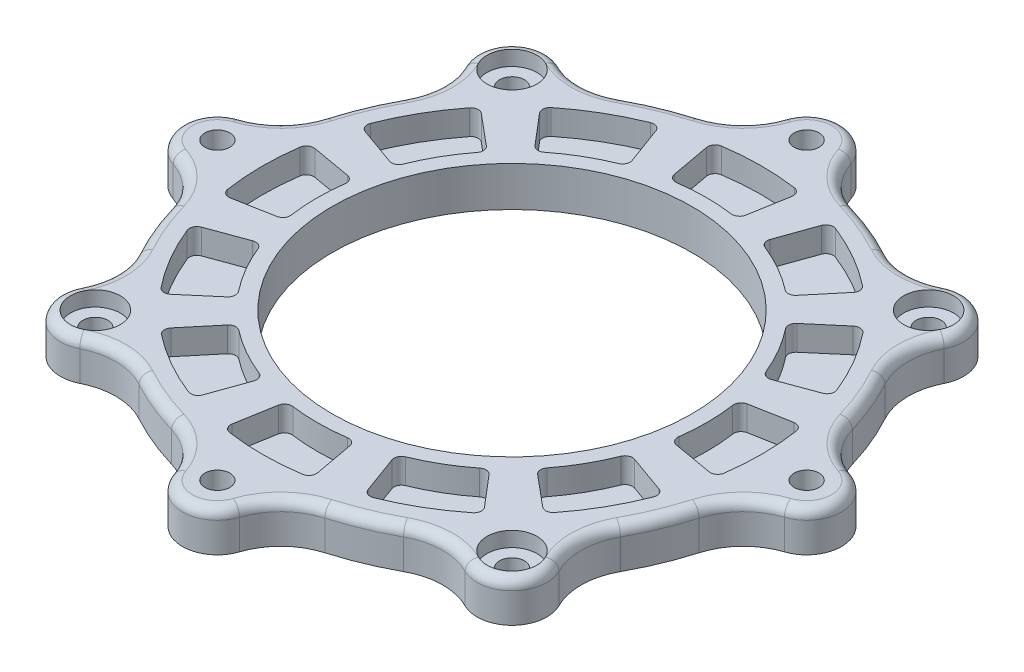
SolidWorks part; units mm, degrees
ref_plane "Front Plane" through (0, 0, 0) normal (0, 0, 1) x (1, 0, 0)
ref_plane "Top Plane" through (0, 0, 0) normal (0, 1, 0) x (1, 0, 0)
ref_plane "Right Plane" through (0, 0, 0) normal (1, 0, 0) x (0, 0, -1)
other "Graphic1"
other "Graphic (Closed) -1"
sketch "Sketch1" plane through (0, 0, 0) normal (0, 1, 0) x (1, 0, 0)
  line L0 (-43.8844, 40.4693) -> (-39.5542, 42.9693)
  circle A0 centre (0, 0) radius 36
  arc A1 (-48.2016, 26.4879) -> (-52.8134, 15.3539) centre (0, 0) ccw
  circle A2 centre (-41.7193, 41.7193) radius 2.5
  arc A3 (-38.5796, 47.9757) -> (-47.9757, 38.5796) centre (-41.7193, 41.7193) ccw
  arc A4 (-47.9757, 38.5796) -> (-48.2016, 26.4879) centre (-59.5947, 32.7487) cw
  arc A5 (-38.5796, 47.9757) -> (-26.4879, 48.2016) centre (-32.7487, 59.5947) ccw
  circle A6 centre (0, 59) radius 2.5
  arc A7 (-6.644, 61.2038) -> (-15.3539, 52.8134) centre (-18.983, 65.2966) cw
  arc A8 (6.644, 61.2038) -> (-6.644, 61.2038) centre (0, 59) ccw
  arc A9 (6.644, 61.2038) -> (15.3539, 52.8134) centre (18.983, 65.2966) ccw
  circle A10 centre (41.7193, 41.7193) radius 2.5
  arc A11 (38.5796, 47.9757) -> (26.4879, 48.2016) centre (32.7487, 59.5947) cw
  arc A12 (47.9757, 38.5796) -> (38.5796, 47.9757) centre (41.7193, 41.7193) ccw
  arc A13 (47.9757, 38.5796) -> (48.2016, 26.4879) centre (59.5947, 32.7487) ccw
  circle A14 centre (59, 0) radius 2.5
  arc A15 (61.2038, 6.644) -> (52.8134, 15.3539) centre (65.2966, 18.983) cw
  arc A16 (61.2038, -6.644) -> (61.2038, 6.644) centre (59, 0) ccw
  arc A17 (61.2038, -6.644) -> (52.8134, -15.3539) centre (65.2966, -18.983) ccw
  circle A18 centre (41.7193, -41.7193) radius 2.5
  arc A19 (47.9757, -38.5796) -> (48.2016, -26.4879) centre (59.5947, -32.7487) cw
  arc A20 (38.5796, -47.9757) -> (47.9757, -38.5796) centre (41.7193, -41.7193) ccw
  arc A21 (38.5796, -47.9757) -> (26.4879, -48.2016) centre (32.7487, -59.5947) ccw
  circle A22 centre (0, -59) radius 2.5
  arc A23 (6.644, -61.2038) -> (15.3539, -52.8134) centre (18.983, -65.2966) cw
  arc A24 (-6.644, -61.2038) -> (6.644, -61.2038) centre (0, -59) ccw
  arc A25 (-6.644, -61.2038) -> (-15.3539, -52.8134) centre (-18.983, -65.2966) ccw
  circle A26 centre (-41.7193, -41.7193) radius 2.5
  arc A27 (-38.5796, -47.9757) -> (-26.4879, -48.2016) centre (-32.7487, -59.5947) cw
  arc A28 (-47.9757, -38.5796) -> (-38.5796, -47.9757) centre (-41.7193, -41.7193) ccw
  arc A29 (-47.9757, -38.5796) -> (-48.2016, -26.4879) centre (-59.5947, -32.7487) ccw
  circle A30 centre (-59, 0) radius 2.5
  arc A31 (-61.2038, -6.644) -> (-52.8134, -15.3539) centre (-65.2966, -18.983) cw
  arc A32 (-61.2038, 6.644) -> (-61.2038, -6.644) centre (-59, 0) ccw
  arc A33 (-61.2038, 6.644) -> (-52.8134, 15.3539) centre (-65.2966, 18.983) ccw
  arc A34 (-52.8134, -15.3539) -> (-48.2016, -26.4879) centre (0, 0) ccw
  arc A35 (-26.4879, -48.2016) -> (-15.3539, -52.8134) centre (0, 0) ccw
  arc A36 (15.3539, -52.8134) -> (26.4879, -48.2016) centre (0, 0) ccw
  arc A37 (48.2016, -26.4879) -> (52.8134, -15.3539) centre (0, 0) ccw
  arc A38 (52.8134, 15.3539) -> (48.2016, 26.4879) centre (0, 0) ccw
  arc A39 (26.4879, 48.2016) -> (15.3539, 52.8134) centre (0, 0) ccw
  arc A40 (-15.3539, 52.8134) -> (-26.4879, 48.2016) centre (0, 0) ccw
  point P74 (0, 0)
  dimension "D1" = 13
  dimension "D2" = 8
extrude "Boss-Extrude1" add sketch "Sketch1" against normal blind 8 contours A7 A40 A5 A3 A4 A1 A33 A32 A31 A34 A29 A28 A27 A35 A25 A24 A23 A36 A21 A20 A19 A37 A17 A16 A15 A38 A13 A12 A11 A39 A9 A8 A0 A2 A6 A10 A14 A18 A22 A26 A30
sketch "Sketch2" plane through (0, 0, 0) normal (0, 1, 0) x (1, 0, 0)
  line L0 (-45.6653, 16.2691) -> (-38.1249, 13.5827)
  line L1 (-37.2162, 31.0637) -> (-31.071, 25.9344)
  line L2 (-31.4127, 36.9221) -> (-26.2258, 30.8254)
  line L3 (-16.6983, 45.5101) -> (-13.9411, 37.9954)
  line L4 (-8.7432, 47.6818) -> (-7.2995, 39.8085)
  line L5 (8.2939, 47.762) -> (6.9244, 39.8755)
  line L6 (16.2691, 45.6653) -> (13.5827, 38.1249)
  line L7 (31.0637, 37.2162) -> (25.9344, 31.071)
  line L8 (36.9221, 31.4127) -> (30.8254, 26.2258)
  line L9 (45.5101, 16.6983) -> (37.9954, 13.9411)
  line L10 (47.6818, 8.7432) -> (39.8085, 7.2995)
  line L11 (47.762, -8.2939) -> (39.8755, -6.9244)
  line L12 (45.6653, -16.2691) -> (38.1249, -13.5827)
  line L13 (37.2162, -31.0637) -> (31.071, -25.9344)
  line L14 (31.4127, -36.9221) -> (26.2258, -30.8254)
  line L15 (16.6983, -45.5101) -> (13.9411, -37.9954)
  line L16 (8.7432, -47.6818) -> (7.2995, -39.8085)
  line L17 (-8.2939, -47.762) -> (-6.9244, -39.8755)
  line L18 (-16.2691, -45.6653) -> (-13.5827, -38.1249)
  line L19 (-31.0637, -37.2162) -> (-25.9344, -31.071)
  line L20 (-36.9221, -31.4127) -> (-30.8254, -26.2258)
  line L21 (-45.5101, -16.6983) -> (-37.9954, -13.9411)
  line L22 (-47.6818, -8.7432) -> (-39.8085, -7.2995)
  line L23 (-47.762, 8.2939) -> (-39.8755, 6.9244)
  arc A0 (-30.8458, 23.865) -> (-36.2281, 14.4403) centre (0, 0) ccw
  arc A2 (-39.3581, 30.8373) -> (-46.5586, 18.229) centre (0, 0) ccw
  arc A3 (-45.6653, 16.2691) -> (-46.5586, 18.229) centre (-45.1619, 17.6821) cw
  arc A4 (-38.1249, 13.5827) -> (-36.2281, 14.4403) centre (-37.6215, 14.9957) ccw
  arc A5 (-31.071, 25.9344) -> (-30.8458, 23.865) centre (-32.0322, 24.7828) cw
  arc A6 (-37.2162, 31.0637) -> (-39.3581, 30.8373) centre (-38.1774, 29.9121) ccw
  arc A7 (-18.6665, 46.3849) -> (-31.2065, 39.066) centre (0, 0) ccw
  arc A8 (-16.6983, 45.5101) -> (-18.6665, 46.3849) centre (-18.1065, 44.9934) ccw
  arc A9 (-31.4127, 36.9221) -> (-31.2065, 39.066) centre (-30.2703, 37.8941) cw
  arc A10 (-26.2258, 30.8254) -> (-24.1543, 30.6197) centre (-25.0833, 31.7974) ccw
  arc A11 (-14.7808, 36.0906) -> (-24.1543, 30.6197) centre (0, 0) ccw
  arc A12 (-13.9411, 37.9954) -> (-14.7808, 36.0906) centre (-15.3493, 37.4787) cw
  arc A13 (7.0268, 49.5038) -> (-7.4926, 49.4354) centre (0, 0) ccw
  arc A14 (8.2939, 47.762) -> (7.0268, 49.5038) centre (6.816, 48.0187) ccw
  arc A15 (-8.7432, 47.6818) -> (-7.4926, 49.4354) centre (-7.2678, 47.9524) cw
  arc A16 (-7.2995, 39.8085) -> (-5.6084, 38.5946) centre (-5.8241, 40.079) ccw
  arc A17 (5.2448, 38.6457) -> (-5.6084, 38.5946) centre (0, 0) ccw
  arc A18 (6.9244, 39.8755) -> (5.2448, 38.6457) centre (5.4465, 40.1321) cw
  arc A19 (30.8373, 39.3581) -> (18.229, 46.5586) centre (0, 0) ccw
  arc A20 (31.0637, 37.2162) -> (30.8373, 39.3581) centre (29.9121, 38.1774) ccw
  arc A21 (16.2691, 45.6653) -> (18.229, 46.5586) centre (17.6821, 45.1619) cw
  arc A22 (13.5827, 38.1249) -> (14.4403, 36.2281) centre (14.9957, 37.6215) ccw
  arc A23 (23.865, 30.8458) -> (14.4403, 36.2281) centre (0, 0) ccw
  arc A24 (25.9344, 31.071) -> (23.865, 30.8458) centre (24.7828, 32.0322) cw
  arc A25 (46.3849, 18.6665) -> (39.066, 31.2065) centre (0, 0) ccw
  arc A26 (45.5101, 16.6983) -> (46.3849, 18.6665) centre (44.9934, 18.1065) ccw
  arc A27 (36.9221, 31.4127) -> (39.066, 31.2065) centre (37.8941, 30.2703) cw
  arc A28 (30.8254, 26.2258) -> (30.6197, 24.1543) centre (31.7974, 25.0833) ccw
  arc A29 (36.0906, 14.7808) -> (30.6197, 24.1543) centre (0, 0) ccw
  arc A30 (37.9954, 13.9411) -> (36.0906, 14.7808) centre (37.4787, 15.3493) cw
  arc A31 (49.5038, -7.0268) -> (49.4354, 7.4926) centre (0, 0) ccw
  arc A32 (47.762, -8.2939) -> (49.5038, -7.0268) centre (48.0187, -6.816) ccw
  arc A33 (47.6818, 8.7432) -> (49.4354, 7.4926) centre (47.9524, 7.2678) cw
  arc A34 (39.8085, 7.2995) -> (38.5946, 5.6084) centre (40.079, 5.8241) ccw
  arc A35 (38.6457, -5.2448) -> (38.5946, 5.6084) centre (0, 0) ccw
  arc A36 (39.8755, -6.9244) -> (38.6457, -5.2448) centre (40.1321, -5.4465) cw
  arc A37 (39.3581, -30.8373) -> (46.5586, -18.229) centre (0, 0) ccw
  arc A38 (37.2162, -31.0637) -> (39.3581, -30.8373) centre (38.1774, -29.9121) ccw
  arc A39 (45.6653, -16.2691) -> (46.5586, -18.229) centre (45.1619, -17.6821) cw
  arc A40 (38.1249, -13.5827) -> (36.2281, -14.4403) centre (37.6215, -14.9957) ccw
  arc A41 (30.8458, -23.865) -> (36.2281, -14.4403) centre (0, 0) ccw
  arc A42 (31.071, -25.9344) -> (30.8458, -23.865) centre (32.0322, -24.7828) cw
  arc A43 (18.6665, -46.3849) -> (31.2065, -39.066) centre (0, 0) ccw
  arc A44 (16.6983, -45.5101) -> (18.6665, -46.3849) centre (18.1065, -44.9934) ccw
  arc A45 (31.4127, -36.9221) -> (31.2065, -39.066) centre (30.2703, -37.8941) cw
  arc A46 (26.2258, -30.8254) -> (24.1543, -30.6197) centre (25.0833, -31.7974) ccw
  arc A47 (14.7808, -36.0906) -> (24.1543, -30.6197) centre (0, 0) ccw
  arc A48 (13.9411, -37.9954) -> (14.7808, -36.0906) centre (15.3493, -37.4787) cw
  arc A49 (-7.0268, -49.5038) -> (7.4926, -49.4354) centre (0, 0) ccw
  arc A50 (-8.2939, -47.762) -> (-7.0268, -49.5038) centre (-6.816, -48.0187) ccw
  arc A51 (8.7432, -47.6818) -> (7.4926, -49.4354) centre (7.2678, -47.9524) cw
  arc A52 (7.2995, -39.8085) -> (5.6084, -38.5946) centre (5.8241, -40.079) ccw
  arc A53 (-5.2448, -38.6457) -> (5.6084, -38.5946) centre (0, 0) ccw
  arc A54 (-6.9244, -39.8755) -> (-5.2448, -38.6457) centre (-5.4465, -40.1321) cw
  arc A55 (-30.8373, -39.3581) -> (-18.229, -46.5586) centre (0, 0) ccw
  arc A56 (-31.0637, -37.2162) -> (-30.8373, -39.3581) centre (-29.9121, -38.1774) ccw
  arc A57 (-16.2691, -45.6653) -> (-18.229, -46.5586) centre (-17.6821, -45.1619) cw
  arc A58 (-13.5827, -38.1249) -> (-14.4403, -36.2281) centre (-14.9957, -37.6215) ccw
  arc A59 (-23.865, -30.8458) -> (-14.4403, -36.2281) centre (0, 0) ccw
  arc A60 (-25.9344, -31.071) -> (-23.865, -30.8458) centre (-24.7828, -32.0322) cw
  arc A61 (-46.3849, -18.6665) -> (-39.066, -31.2065) centre (0, 0) ccw
  arc A62 (-45.5101, -16.6983) -> (-46.3849, -18.6665) centre (-44.9934, -18.1065) ccw
  arc A63 (-36.9221, -31.4127) -> (-39.066, -31.2065) centre (-37.8941, -30.2703) cw
  arc A64 (-30.8254, -26.2258) -> (-30.6197, -24.1543) centre (-31.7974, -25.0833) ccw
  arc A65 (-36.0906, -14.7808) -> (-30.6197, -24.1543) centre (0, 0) ccw
  arc A66 (-37.9954, -13.9411) -> (-36.0906, -14.7808) centre (-37.4787, -15.3493) cw
  arc A67 (-49.5038, 7.0268) -> (-49.4354, -7.4926) centre (0, 0) ccw
  arc A68 (-47.762, 8.2939) -> (-49.5038, 7.0268) centre (-48.0187, 6.816) ccw
  arc A69 (-47.6818, -8.7432) -> (-49.4354, -7.4926) centre (-47.9524, -7.2678) cw
  arc A70 (-39.8085, -7.2995) -> (-38.5946, -5.6084) centre (-40.079, -5.8241) ccw
  arc A71 (-38.6457, 5.2448) -> (-38.5946, -5.6084) centre (0, 0) ccw
  arc A72 (-39.8755, 6.9244) -> (-38.6457, 5.2448) centre (-40.1321, 5.4465) cw
  point P148 (0, 0)
  dimension "D1" = 1.5
  dimension "D2" = 12
extrude "Cut-Extrude2" cut sketch "Sketch2" against normal blind 5
fillet "Fillet1" radius 2 32 edges at (-32.5059, 0, 46.5969) (-46.669, 0, 46.669) (-46.5969, 0, 32.5059) (-50.8134, 0, 21.0476) (-55.9341, 0, 9.9639) (-66, 0, 0) (-55.9341, 0, -9.9639) (-50.8134, 0, -21.0476) (-46.5969, 0, -32.5059) (-46.669, 0, -46.669) (-32.5059, 0, -46.5969) (-21.0476, 0, -50.8134) (-9.9639, 0, -55.9341) (0, 0, -66) (9.9639, 0, -55.9341) (21.0476, 0, -50.8134) (32.5059, 0, -46.5969) (46.669, 0, -46.669) (46.5969, 0, -32.5059) (50.8134, 0, -21.0476) (55.9341, 0, -9.9639) (66, 0, 0) (55.9341, 0, 9.9639) (50.8134, 0, 21.0476) (46.5969, 0, 32.5059) (46.669, 0, 46.669) (32.5059, 0, 46.5969) (21.0476, 0, 50.8134) (9.9639, 0, 55.9341) (0, 0, 66) (-9.9639, 0, 55.9341) (-21.0476, 0, 50.8134)
sketch "Sketch3" plane through (0, 0, 0) normal (0, 1, 0) x (1, 0, 0)
  circle A0 centre (-41.7193, -41.7193) radius 5
  circle A1 centre (-41.7193, 41.7193) radius 5
  circle A2 centre (41.7193, 41.7193) radius 5
  circle A3 centre (41.7193, -41.7193) radius 5
  point P12 (0, 0)
  dimension "D1" = 4
extrude "Cut-Extrude3" cut sketch "Sketch3" against normal blind 3
